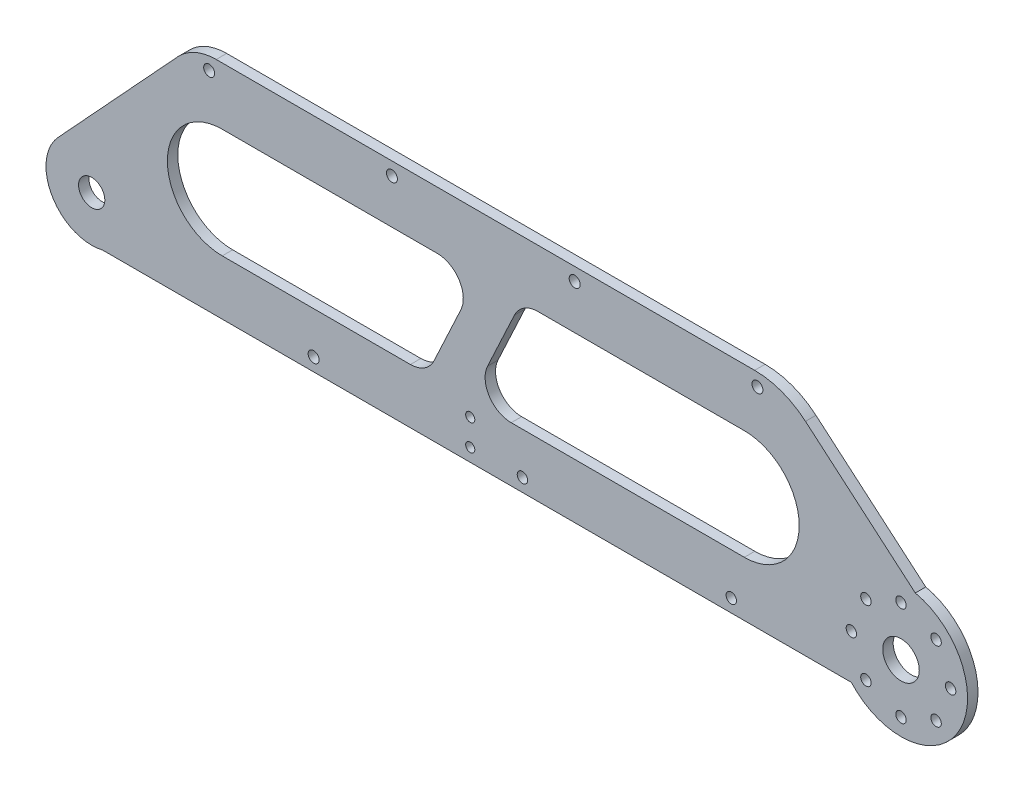
SolidWorks part; units mm, degrees
ref_plane "前视基准面" through (0, 0, 0) normal (0, 0, 1) x (1, 0, 0)
ref_plane "上视基准面" through (0, 0, 0) normal (0, 1, 0) x (1, 0, 0)
ref_plane "右视基准面" through (0, 0, 0) normal (1, 0, 0) x (0, 0, -1)
sketch "草图2" plane through (0, 0, 0) normal (0, 0, 1) x (1, 0, 0)
  line L0 (-262.3052, 68) -> (-56.0638, 68)
  line L1 (-149.3031, 4) -> (-60, 4)
  line L2 (-60, 46) -> (-139.0444, 46)
  line L3 (-148.1075, 40.2262) -> (-158.3662, 18.2262)
  line L6 (-178.8583, 9.7738) -> (-168.5995, 31.7738)
  line L7 (-260, 4) -> (-187.9214, 4)
  line L8 (-177.6626, 46) -> (-260, 46)
  line L9 (-322.861, 11.8678) -> (-277.0035, 61.5632)
  line L10 (-305.8467, -17) -> (-19.0066, -17)
  line L11 (-36.5854, 60.8165) -> (5.4821, 24.9037)
  line L12 (-310, 0) -> (0, 0) construction
  circle A0 centre (-55, 63) radius 2.1
  circle A1 centre (-195, 63) radius 2.1
  circle A2 centre (0, 0) radius 7
  circle A3 centre (-265, 63) radius 2.1
  circle A4 centre (-225, -12) radius 2.1
  circle A5 centre (-65, -12) radius 2
  circle A6 centre (-310, 0) radius 5.03
  circle A7 centre (-125, 63) radius 2.1
  circle A8 centre (-145, -12) radius 2
  circle A11 centre (-165, -2) radius 1.75
  circle A12 centre (-165, -12) radius 1.75
  circle A13 centre (0, -19) radius 2
  circle A14 centre (-13.435, -13.435) radius 2
  circle A15 centre (-19, 0) radius 2
  circle A16 centre (-13.435, 13.435) radius 2
  arc A17 (-36.5854, 60.8165) -> (-56.0638, 68) centre (-56.0638, 38) ccw
  arc A18 (-262.3052, 68) -> (-277.0035, 61.5632) centre (-262.3052, 48) ccw
  arc A19 (-158.3662, 18.2262) -> (-149.3031, 4) centre (-149.3031, 14) ccw
  arc A20 (-60, 4) -> (-60, 46) centre (-60, 25) ccw
  arc A21 (-139.0444, 46) -> (-148.1075, 40.2262) centre (-139.0444, 36) ccw
  arc A22 (-322.861, 11.8678) -> (-305.8467, -17) centre (-310, 0) ccw
  arc A24 (-187.9214, 4) -> (-178.8583, 9.7738) centre (-187.9214, 14) ccw
  arc A25 (-260, 46) -> (-260, 4) centre (-260, 25) ccw
  arc A26 (-168.5995, 31.7738) -> (-177.6626, 46) centre (-177.6626, 36) ccw
  circle A27 centre (0, 0) radius 19 construction
  circle A28 centre (0, 19) radius 2
  circle A29 centre (13.435, 13.435) radius 2
  circle A30 centre (19, 0) radius 2
  circle A31 centre (13.435, -13.435) radius 2
  circle A32 centre (0, 0) radius 25.5 construction
  arc A33 (-19.0066, -17) -> (5.4821, 24.9037) centre (0, 0) ccw
  dimension "D1" = 8
extrude "凸台-拉伸1" add sketch "草图2" along normal blind 4 separate body contours L0 A17 A22 L9 A18
